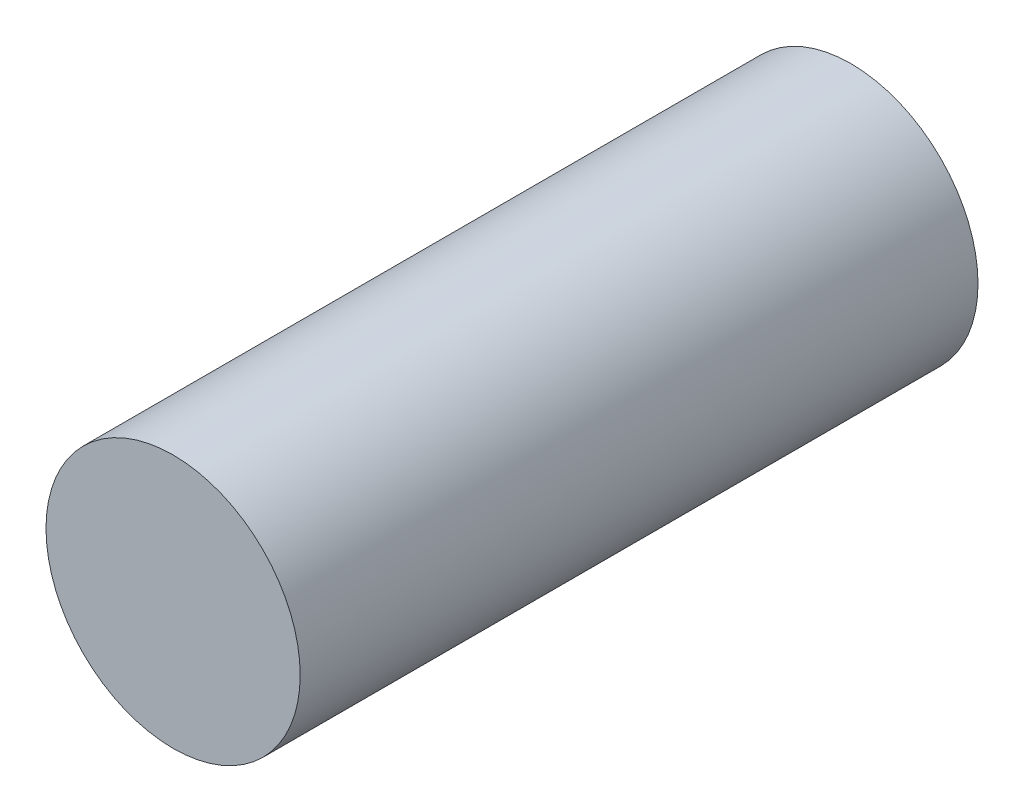
SolidWorks part; units mm, degrees
ref_plane "Front Plane" through (0, 0, 0) normal (0, 0, 1) x (1, 0, 0)
ref_plane "Top Plane" through (0, 0, 0) normal (0, 1, 0) x (1, 0, 0)
ref_plane "Right Plane" through (0, 0, 0) normal (1, 0, 0) x (0, 0, -1)
sketch "Sketch2" plane through (0, 0, 0) normal (0, 0, 1) x (1, 0, 0)
  circle A0 centre (0, 0) radius 4.7625
  dimension "D1" = 9.525
extrude "Boss-Extrude1" add sketch "Sketch2" along normal blind 25.4
